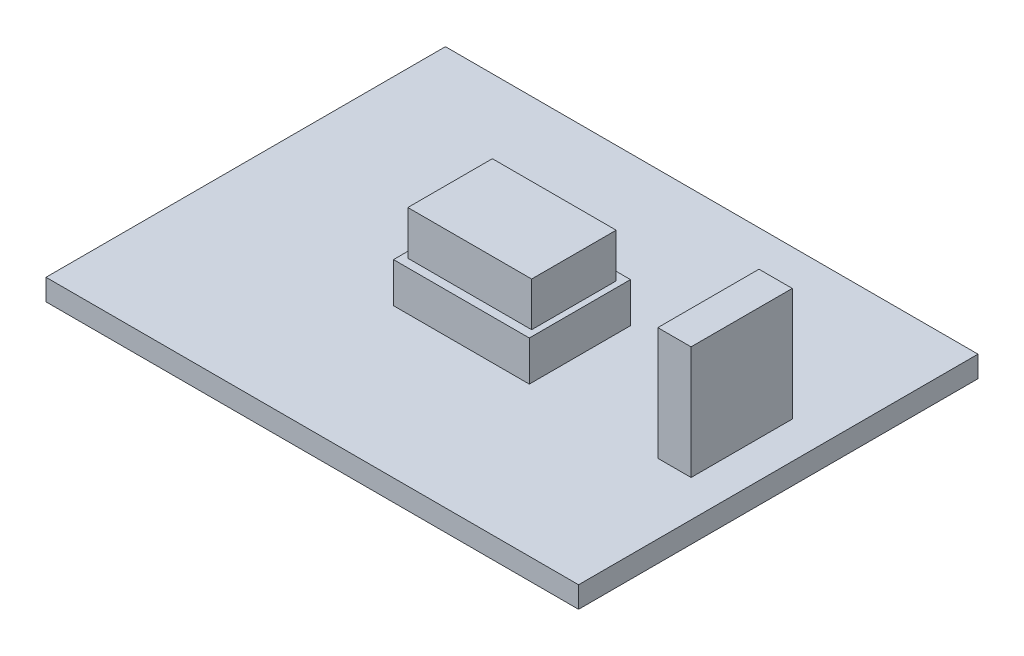
SolidWorks part; units mm, degrees
ref_plane "Front Plane" through (0, 0, 0) normal (0, 0, 1) x (1, 0, 0)
ref_plane "Top Plane" through (0, 0, 0) normal (0, 1, 0) x (1, 0, 0)
ref_plane "Right Plane" through (0, 0, 0) normal (1, 0, 0) x (0, 0, -1)
other "Configuration Table"
sketch "Sketch1" plane through (0, 0, 0) normal (0, 1, 0) x (1, 0, 0)
  line L0 (-20, -15) -> (20, -15)
  line L1 (20, -15) -> (20, 15)
  line L2 (20, 15) -> (-20, 15)
  line L3 (-20, 15) -> (-20, -15)
extrude "Perfboard" add sketch "Sketch1" along normal blind 1.6
sketch "Sketch2" plane through (0, 0, 0) normal (0, 1, 0) x (1, 0, 0)
  line L0 (-5.1, -3.8) -> (5.1, -3.8)
  line L1 (5.1, -3.8) -> (5.1, 3.8)
  line L2 (5.1, 3.8) -> (-5.1, 3.8)
  line L3 (-5.1, 3.8) -> (-5.1, -3.8)
extrude "DIP8_Socket" add sketch "Sketch2" along normal blind 3 from offset 1.6
sketch "Sketch3" plane through (0, 0, 0) normal (0, 1, 0) x (1, 0, 0)
  line L0 (-4.65, -3.175) -> (4.65, -3.175)
  line L1 (4.65, -3.175) -> (4.65, 3.175)
  line L2 (4.65, 3.175) -> (-4.65, 3.175)
  line L3 (-4.65, 3.175) -> (-4.65, -3.175)
extrude "CA3140" add sketch "Sketch3" along normal blind 3.3 from offset 4.6
sketch "Sketch4" plane through (0, 0, 0) normal (0, 1, 0) x (1, 0, 0)
  line L0 (14.75, -3.8) -> (17.25, -3.8)
  line L1 (17.25, -3.8) -> (17.25, 3.8)
  line L2 (17.25, 3.8) -> (14.75, 3.8)
  line L3 (14.75, 3.8) -> (14.75, -3.8)
extrude "Header" add sketch "Sketch4" along normal blind 8.5 from offset 1.6
equation "\"Jar_OD\"= 90  'ASSUMED - Part G fallback - jar outer diameter"
equation "\"Jar_H\"= 120  'ASSUMED - Part G fallback - jar height"
equation "\"Pump_L\"= 45  'ASSUMED - Part G fallback"
equation "\"Pump_W\"= 24  'ASSUMED - Part G fallback"
equation "\"Pump_H\"= 33  'ASSUMED - Part G fallback"
equation "\"Pump_Outlet_OD\"= 7.5  'ASSUMED - Part G fallback"
equation "\"Tube_OD\"= 8  'ASSUMED - Part G fallback"
equation "\"Tube_ID\"= 6  'ASSUMED - Part G fallback"
equation "\"TDS_Body_Dia\"= 12  'ASSUMED - Part G fallback"
equation "\"TDS_Wet_Len\"= 45  'ASSUMED - Part G fallback - length in water"
equation "\"DS_Tube_Dia\"= 6  'ASSUMED - Part G fallback"
equation "\"DS_Tube_Len\"= 50  'ASSUMED - Part G fallback"
equation "\"ORP_Body_Dia\"= 12  'ASSUMED - Part G fallback"
equation "\"ORP_Body_Len\"= 150  'ASSUMED - Part G fallback"
equation "\"ORP_Cap_Dia\"= 16  'ASSUMED - Part G fallback"
equation "\"Turb_W\"= 33  'ASSUMED - Part G fallback - head width"
equation "\"Turb_D\"= 28  'ASSUMED - Part G fallback - head depth"
equation "\"Turb_H\"= 30  'ASSUMED - Part G fallback - head height"
equation "\"Turb_Slot_W\"= 10  'ASSUMED - Part G fallback - slot width"
equation "\"Flow_L\"= 62  'ASSUMED - Part G fallback YF-S201"
equation "\"Flow_W\"= 36  'ASSUMED - Part G fallback"
equation "\"Flow_H\"= 35  'ASSUMED - Part G fallback"
equation "\"Thread_G12_OD\"= 20.955  'ASSUMED - Part G fallback thread G1/2 (major diameter)"
equation "\"Valve_L\"= 75  'ASSUMED - Part G fallback"
equation "\"Valve_W\"= 45  'ASSUMED - Part G fallback"
equation "\"Valve_H\"= 60  'ASSUMED - Part G fallback"
equation "\"Tee_L\"= 40  'ASSUMED - Part G fallback - overall length"
equation "\"Tee_Branch_L\"= 25  'ASSUMED - Part G fallback"
equation "\"Tee_OD\"= 12  'ASSUMED - Part G fallback"
equation "\"Cuv_W\"= 12.5  'ASSUMED - old R3 cuvette (station suppressed in SS4)"
equation "\"Cuv_D\"= 12.5  'ASSUMED - old R3 cuvette (station suppressed in SS4)"
equation "\"Cuv_H\"= 45  'ASSUMED - old R3 cuvette (station suppressed in SS4)"
equation "\"LED_Board_L\"= 20  'ASSUMED - Part G fallback"
equation "\"LED_Board_W\"= 20  'ASSUMED - Part G fallback - LED at centre"
equation "\"GUVA_L\"= 20  'ASSUMED - Part G fallback"
equation "\"GUVA_W\"= 12  'ASSUMED - Part G fallback - sensor at centre"
equation "\"Reed_L\"= 27  'ASSUMED - Part G fallback MC-38 half"
equation "\"Reed_W\"= 14  'ASSUMED - Part G fallback"
equation "\"Reed_H\"= 8  'ASSUMED - Part G fallback"
equation "\"ESP_L\"= 51  'ASSUMED - Part G fallback"
equation "\"ESP_W\"= 28  'ASSUMED - Part G fallback"
equation "\"TFT_L\"= 58  'ASSUMED - Part G fallback - board"
equation "\"TFT_W\"= 35  'ASSUMED - Part G fallback - board"
equation "\"TFT_Win_L\"= 35  'ASSUMED - Part G fallback - visible window"
equation "\"TFT_Win_W\"= 28  'ASSUMED - Part G fallback - visible window"
equation "\"Relay_L\"= 50  'ASSUMED - Part G fallback"
equation "\"Relay_W\"= 26  'ASSUMED - Part G fallback"
equation "\"Relay_H\"= 19  'ASSUMED - Part G fallback"
equation "\"Mosfet_L\"= 34  'ASSUMED - Part G fallback"
equation "\"Mosfet_W\"= 17  'ASSUMED - Part G fallback"
equation "\"Mosfet_H\"= 12  'ASSUMED - Part G fallback"
equation "\"TDS_Board_L\"= 42  'ASSUMED - Part G fallback"
equation "\"TDS_Board_W\"= 32  'ASSUMED - Part G fallback"
equation "\"Turb_Board_L\"= 38  'ASSUMED - Part G fallback"
equation "\"Turb_Board_W\"= 28  'ASSUMED - Part G fallback"
equation "\"BNC_Thread_Dia\"= 9.5  'ASSUMED - Part G fallback"
equation "\"Plate_L\"= 420  'ASSUMED - Part G fallback"
equation "\"Plate_W\"= 297  'ASSUMED - Part G fallback"
equation "\"Plate_T\"= 6  'ASSUMED - Part G fallback"
equation "\"Probe_Clr\"= 0.3  'DESIGN VALUE - Part C rule 3 - printed probe hole = diameter + 0.3"
equation "\"Cuv_Clr\"= 0.2  'DESIGN VALUE - Part C rule 3 - cuvette pocket = size + 0.2"
equation "\"Label_H\"= 0.6  'DESIGN VALUE - Part D - raised label height"
equation "\"Booster_L\"= 150  'ASSUMED - Part G fallback - booster pump"
equation "\"Booster_W\"= 95  'ASSUMED - Part G fallback"
equation "\"Booster_H\"= 100  'ASSUMED - Part G fallback"
equation "\"PTube_OD\"= 6.35  'ASSUMED - Part G fallback - product tube 1/4 inch"
equation "\"Qz_Out\"= 12  'ASSUMED - Part G fallback - quartz channel outside square"
equation "\"Qz_Path\"= 10  'ASSUMED - Part G fallback - quartz channel inside light path"
equation "\"Qz_L\"= 40  'ASSUMED - Part G fallback - quartz channel length"
equation "\"LED860_Dia\"= 5  'ASSUMED - Part G fallback - 860 nm LED"
equation "\"BPW_L\"= 5.4  'ASSUMED - Part G fallback - BPW34"
equation "\"BPW_W\"= 4.3  'ASSUMED - Part G fallback - BPW34"
equation "\"Cart_Dia\"= 50  'ASSUMED - Part G fallback - sediment and pre-carbon cartridges"
equation "\"Cart_L\"= 255  'ASSUMED - Part G fallback"
equation "\"UF_Dia\"= 50  'ASSUMED - Part G fallback - UF cartridge"
equation "\"UF_L\"= 260  'ASSUMED - Part G fallback"
equation "\"RO_Dia\"= 62  'ASSUMED - Part G fallback - RO membrane housing"
equation "\"RO_L\"= 300  'ASSUMED - Part G fallback"
equation "\"UVC_Dia\"= 40  'ASSUMED - Part G fallback - UV-C chamber"
equation "\"UVC_L\"= 300  'ASSUMED - Part G fallback"
equation "\"Tank_W\"= 260  'ASSUMED - Part G fallback - storage tank"
equation "\"Tank_D\"= 160  'ASSUMED - Part G fallback"
equation "\"Tank_H\"= 300  'ASSUMED - Part G fallback"
equation "\"Cab_W\"= 400  'ASSUMED - Part G fallback - purifier cabinet"
equation "\"Cab_D\"= 270  'ASSUMED - Part G fallback"
equation "\"Cab_H\"= 560  'ASSUMED - Part G fallback"
equation "\"ORP_Board_L\"= 40  'ASSUMED - Part G fallback - ORP buffer board"
equation "\"ORP_Board_W\"= 30  'ASSUMED - Part G fallback"
equation "\"Opt_Board_L\"= 50  'ASSUMED - Part G fallback - optical front-end board"
equation "\"Opt_Board_W\"= 40  'ASSUMED - Part G fallback"
equation "\"Buck_L\"= 43  'ASSUMED - Part G fallback - 12 V to 5 V buck module"
equation "\"Buck_W\"= 21  'ASSUMED - Part G fallback"
equation "\"Buck_H\"= 14  'ASSUMED - Part G fallback"
equation "\"BB_L\"= 165  'ASSUMED - Part G fallback - breadboard (As_Built_R3 only)"
equation "\"BB_W\"= 55  'ASSUMED - Part G fallback"
equation "\"BB_H\"= 10  'ASSUMED - Part G fallback"
